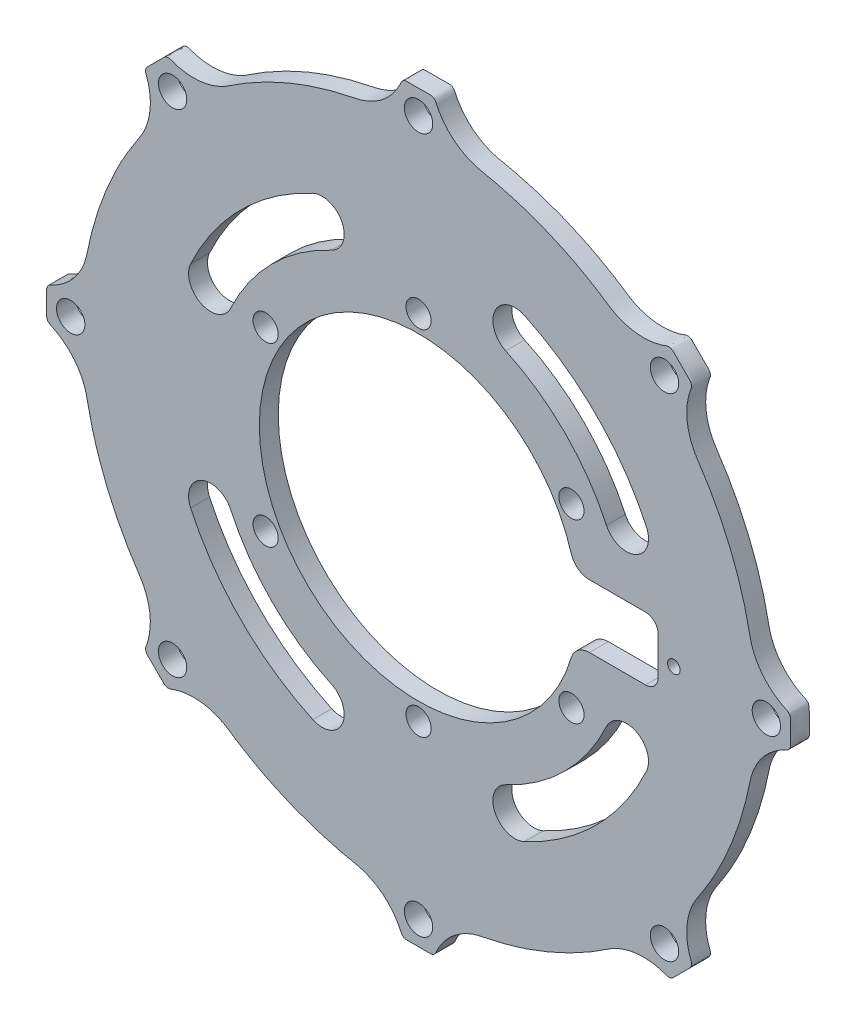
SolidWorks part; units mm, degrees
material "6061-T6 (SS)"
ref_plane "Front Plane" through (0, 0, 0) normal (0, 0, 1) x (1, 0, 0)
ref_plane "Top Plane" through (0, 0, 0) normal (0, 1, 0) x (1, 0, 0)
ref_plane "Right Plane" through (0, 0, 0) normal (1, 0, 0) x (0, 0, -1)
sketch "Sketch1" plane through (0, 0, 0) normal (0, 0, 1) x (1, 0, 0)
  line L0 (0, 0) -> (15.2936, 32.9713) construction
  line L1 (-3.9972, 40.3023) -> (0, 28) construction
  line L3 (38, -3) -> (38, 3) construction
  line L4 (38, -3) -> (38, 3)
  line L5 (36, 5) -> (27.0936, 5)
  line L6 (36, -5) -> (27.0936, -5)
  line L7 (0, 0) -> (0, 48) construction
  line L8 (-2.8886, 58.0903) -> (-2.7624, 58.3675)
  line L9 (-1.8466, 58.9658) -> (1.8466, 58.9658) construction
  line L10 (2.7624, 58.3675) -> (2.7687, 58.3533)
  line L11 (-5, 53.2658) -> (5, 53.2658) construction
  line L12 (40.3894, 43.0009) -> (43.0009, 40.3894) construction
  line L13 (39.3043, 43.2198) -> (39.3187, 43.2254) construction
  line L14 (43.2254, 39.3187) -> (43.2198, 39.3043) construction
  line L15 (58.9658, 1.8466) -> (58.9658, -1.8466) construction
  line L16 (58.3533, 2.7687) -> (58.3675, 2.7624) construction
  line L17 (58.3675, -2.7624) -> (58.3533, -2.7687) construction
  line L18 (43.0009, -40.3894) -> (40.3894, -43.0009) construction
  line L19 (43.2198, -39.3043) -> (43.2254, -39.3187) construction
  line L20 (39.3187, -43.2254) -> (39.3043, -43.2198) construction
  line L21 (1.8466, -58.9658) -> (-1.8466, -58.9658) construction
  line L22 (2.7687, -58.3533) -> (2.7624, -58.3675) construction
  line L23 (-2.7624, -58.3675) -> (-2.7687, -58.3533) construction
  line L24 (-40.3894, -43.0009) -> (-43.0009, -40.3894) construction
  line L25 (-39.3043, -43.2198) -> (-39.3187, -43.2254) construction
  line L26 (-43.2254, -39.3187) -> (-43.2198, -39.3043) construction
  line L27 (-58.9658, -1.8466) -> (-58.9658, 1.8466) construction
  line L28 (-58.3533, -2.7687) -> (-58.3675, -2.7624) construction
  line L29 (-58.3675, 2.7624) -> (-58.3533, 2.7687) construction
  line L30 (-43.0009, 40.3894) -> (-40.3894, 43.0009) construction
  line L31 (-43.2198, 39.3043) -> (-43.2254, 39.3187) construction
  line L32 (-39.3187, 43.2254) -> (-39.3043, 43.2198) construction
  line L33 (0, 0) -> (25.7002, 25.7002) construction
  arc A0 (-10.0483, 52.5479) -> (-30.0517, 44.2622) centre (0, 0) ccw construction
  circle A1 centre (0, 0) radius 28 construction
  arc A3 (24.2164, 7.1504) -> (24.2164, -7.1504) centre (0, 0) ccw
  arc A4 (38, 3) -> (34, 3) centre (36, 3) ccw construction
  arc A5 (34, -3) -> (38, -3) centre (36, -3) ccw construction
  arc A6 (36, -5) -> (38, -3) centre (36, -3) ccw
  arc A7 (38, 3) -> (36, 5) centre (36, 3) ccw
  arc A8 (27.0936, -5) -> (24.2164, -7.1504) centre (27.0936, -8) ccw
  arc A9 (27.0936, 5) -> (24.2164, 7.1504) centre (27.0936, 8) cw
  circle A10 centre (0, 0) radius 36.3456 construction
  arc A13 (15.2936, 32.9713) -> (32.9713, 15.2936) centre (0, 0) cw construction
  circle A72 centre (0, 0) radius 40.5 construction
  circle A81 centre (40.4993, -0.2374) radius 1
  arc A104 (-2.8886, 58.0903) -> (-10.0483, 52.5479) centre (-11.9265, 62.3699) cw construction
  arc A105 (2.7687, 58.3533) -> (10.0483, 52.5479) centre (11.9265, 62.3699) ccw construction
  arc A106 (39.3043, 43.2198) -> (30.0517, 44.2622) centre (35.6689, 52.5355) cw construction
  arc A107 (43.2198, 39.3043) -> (44.2622, 30.0517) centre (52.5355, 35.6689) ccw construction
  arc A108 (58.3533, 2.7687) -> (52.5479, 10.0483) centre (62.3699, 11.9265) cw construction
  arc A109 (58.3533, -2.7687) -> (52.5479, -10.0483) centre (62.3699, -11.9265) ccw construction
  arc A110 (43.2198, -39.3043) -> (44.2622, -30.0517) centre (52.5355, -35.6689) cw construction
  arc A111 (39.3043, -43.2198) -> (30.0517, -44.2622) centre (35.6689, -52.5355) ccw construction
  arc A112 (2.7687, -58.3533) -> (10.0483, -52.5479) centre (11.9265, -62.3699) cw construction
  arc A113 (-2.7687, -58.3533) -> (-10.0483, -52.5479) centre (-11.9265, -62.3699) ccw construction
  arc A114 (-39.3043, -43.2198) -> (-30.0517, -44.2622) centre (-35.6689, -52.5355) cw construction
  arc A115 (-43.2198, -39.3043) -> (-44.2622, -30.0517) centre (-52.5355, -35.6689) ccw construction
  arc A116 (-58.3533, -2.7687) -> (-52.5479, -10.0483) centre (-62.3699, -11.9265) cw construction
  arc A117 (-58.3533, 2.7687) -> (-52.5479, 10.0483) centre (-62.3699, 11.9265) ccw construction
  arc A118 (-43.2198, 39.3043) -> (-44.2622, 30.0517) centre (-52.5355, 35.6689) cw construction
  arc A119 (-39.3043, 43.2198) -> (-30.0517, 44.2622) centre (-35.6689, 52.5355) ccw construction
  arc A120 (30.0517, 44.2622) -> (10.0483, 52.5479) centre (0, 0) ccw construction
  arc A121 (52.5479, 10.0483) -> (44.2622, 30.0517) centre (0, 0) ccw construction
  arc A122 (10.0483, -52.5479) -> (30.0517, -44.2622) centre (0, 0) ccw construction
  arc A123 (44.2622, -30.0517) -> (52.5479, -10.0483) centre (0, 0) ccw construction
  arc A124 (-30.0517, -44.2622) -> (-10.0483, -52.5479) centre (0, 0) ccw construction
  arc A125 (-52.5479, -10.0483) -> (-44.2622, -30.0517) centre (0, 0) ccw construction
  arc A126 (-44.2622, 30.0517) -> (-52.5479, 10.0483) centre (0, 0) ccw construction
  arc A127 (1.8466, 58.9658) -> (2.7624, 58.3675) centre (1.8466, 57.9658) cw construction
  arc A128 (-2.7624, 58.3675) -> (-1.8466, 58.9658) centre (-1.8466, 57.9658) cw construction
  arc A129 (-43.0009, 40.3894) -> (-43.2254, 39.3187) centre (-42.2938, 39.6823) ccw construction
  arc A130 (-40.3894, 43.0009) -> (-39.3187, 43.2254) centre (-39.6823, 42.2938) cw construction
  arc A131 (-58.9658, 1.8466) -> (-58.3675, 2.7624) centre (-57.9658, 1.8466) cw construction
  arc A132 (-58.9658, -1.8466) -> (-58.3675, -2.7624) centre (-57.9658, -1.8466) ccw construction
  arc A133 (-43.0009, -40.3894) -> (-43.2254, -39.3187) centre (-42.2938, -39.6823) cw construction
  arc A134 (-40.3894, -43.0009) -> (-39.3187, -43.2254) centre (-39.6823, -42.2938) ccw construction
  arc A135 (-1.8466, -58.9658) -> (-2.7624, -58.3675) centre (-1.8466, -57.9658) cw construction
  arc A136 (1.8466, -58.9658) -> (2.7624, -58.3675) centre (1.8466, -57.9658) ccw construction
  arc A137 (43.0009, -40.3894) -> (43.2254, -39.3187) centre (42.2938, -39.6823) ccw construction
  arc A138 (40.3894, -43.0009) -> (39.3187, -43.2254) centre (39.6823, -42.2938) cw construction
  arc A139 (58.9658, -1.8466) -> (58.3675, -2.7624) centre (57.9658, -1.8466) cw construction
  arc A140 (58.9658, 1.8466) -> (58.3675, 2.7624) centre (57.9658, 1.8466) ccw construction
  arc A141 (43.0009, 40.3894) -> (43.2254, 39.3187) centre (42.2938, 39.6823) cw construction
  arc A142 (40.3894, 43.0009) -> (39.3187, 43.2254) centre (39.6823, 42.2938) ccw construction
  arc A143 (36.1463, 16.7664) -> (16.7664, 36.1463) centre (0, 0) ccw
  arc A144 (29.7962, 13.8209) -> (13.8209, 29.7962) centre (0, 0) ccw
  arc A145 (29.7962, 13.8209) -> (36.1463, 16.7664) centre (32.9713, 15.2936) ccw
  arc A146 (16.7664, 36.1463) -> (13.8209, 29.7962) centre (15.2936, 32.9713) ccw
  arc A147 (32.9713, -15.2936) -> (15.2936, -32.9713) centre (0, 0) cw construction
  arc A148 (16.7664, -36.1463) -> (36.1463, -16.7664) centre (0, 0) ccw
  arc A149 (13.8209, -29.7962) -> (29.7962, -13.8209) centre (0, 0) ccw
  arc A150 (13.8209, -29.7962) -> (16.7664, -36.1463) centre (15.2936, -32.9713) ccw
  arc A151 (36.1463, -16.7664) -> (29.7962, -13.8209) centre (32.9713, -15.2936) ccw
  arc A152 (-15.2936, -32.9713) -> (-32.9713, -15.2936) centre (0, 0) cw construction
  arc A153 (-36.1463, -16.7664) -> (-16.7664, -36.1463) centre (0, 0) ccw
  arc A154 (-29.7962, -13.8209) -> (-13.8209, -29.7962) centre (0, 0) ccw
  arc A155 (-29.7962, -13.8209) -> (-36.1463, -16.7664) centre (-32.9713, -15.2936) ccw
  arc A156 (-16.7664, -36.1463) -> (-13.8209, -29.7962) centre (-15.2936, -32.9713) ccw
  arc A157 (-32.9713, 15.2936) -> (-15.2936, 32.9713) centre (0, 0) cw construction
  arc A158 (-16.7664, 36.1463) -> (-36.1463, 16.7664) centre (0, 0) ccw
  arc A159 (-13.8209, 29.7962) -> (-29.7962, 13.8209) centre (0, 0) ccw
  arc A160 (-13.8209, 29.7962) -> (-16.7664, 36.1463) centre (-15.2936, 32.9713) ccw
  arc A161 (-36.1463, 16.7664) -> (-29.7962, 13.8209) centre (-32.9713, 15.2936) ccw
  spline S0 degree 3 poles (-2.8886, 58.0903) (-3.9043, 55.9453) (-5.5918, 54.2764) (-7.7481, 53.2847) (-8.2352, 53.0607) (-9.2456, 52.691) (-10.8423, 52.3981) (-11.8892, 52.165) (-12.4107, 52.0406) (-17.936, 50.7229) (-23.1839, 48.5492) (-28.0226, 45.574) (-28.4793, 45.2931) (-29.3844, 44.7177) (-30.7205, 43.7957) (-31.6964, 43.3428) (-32.1993, 43.1567) (-34.5203, 42.2981) (-36.9949, 42.3196) (-39.3007, 43.2183) (-39.3011, 43.2185) (-39.3019, 43.2188) (-39.3031, 43.2193) (-39.3039, 43.2196) (-39.3043, 43.2198) (-39.3047, 43.2199) (-39.3055, 43.2202) (-39.3067, 43.2207) (-39.3075, 43.221) (-39.3079, 43.2212) (-39.3103, 43.2221) (-39.3127, 43.223) (-39.3151, 43.224) (-39.3155, 43.2241) (-39.3163, 43.2245) (-39.3175, 43.2249) (-39.3183, 43.2252) (-39.3187, 43.2254) (-39.3191, 43.2255) (-39.3199, 43.2259) (-39.3211, 43.2263) (-39.3219, 43.2266) (-39.3224, 43.2268) (-39.5998, 43.3338) (-39.8966, 43.3148) (-40.1582, 43.1733) (-40.1864, 43.158) (-40.2413, 43.1248) (-40.3214, 43.0689) (-40.3667, 43.0236) (-40.3894, 43.0009) (-40.412, 42.9783) (-40.4573, 42.933) (-40.5253, 42.865) (-40.5706, 42.8197) (-40.5933, 42.797) (-41.3279, 42.0624) (-42.0624, 41.3279) (-42.797, 40.5933) (-42.8197, 40.5706) (-42.865, 40.5253) (-42.933, 40.4573) (-42.9783, 40.412) (-43.0009, 40.3894) (-43.0236, 40.3667) (-43.0689, 40.3214) (-43.1248, 40.2413) (-43.158, 40.1864) (-43.1733, 40.1582) (-43.3148, 39.8966) (-43.3338, 39.5998) (-43.2268, 39.3224) (-43.2266, 39.3219) (-43.2263, 39.3211) (-43.2259, 39.3199) (-43.2255, 39.3191) (-43.2254, 39.3187) (-43.2252, 39.3183) (-43.2249, 39.3175) (-43.2245, 39.3163) (-43.2241, 39.3155) (-43.224, 39.3151) (-43.223, 39.3127) (-43.2221, 39.3103) (-43.2212, 39.3079) (-43.221, 39.3075) (-43.2207, 39.3067) (-43.2202, 39.3055) (-43.2199, 39.3047) (-43.2198, 39.3043) (-43.2196, 39.3039) (-43.2193, 39.3031) (-43.2188, 39.3019) (-43.2185, 39.3011) (-43.2183, 39.3007) (-42.3196, 36.9949) (-42.2981, 34.5203) (-43.1567, 32.1993) (-43.3428, 31.6964) (-43.7957, 30.7205) (-44.7177, 29.3844) (-45.2931, 28.4793) (-45.574, 28.0226) (-48.5492, 23.1839) (-50.7229, 17.936) (-52.0406, 12.4107) (-52.165, 11.8892) (-52.3981, 10.8423) (-52.691, 9.2456) (-53.0607, 8.2352) (-53.2847, 7.7481) (-54.3188, 5.4997) (-56.0838, 3.7651) (-58.3498, 2.7702) (-58.3502, 2.77) (-58.3509, 2.7697) (-58.3521, 2.7692) (-58.3529, 2.7688) (-58.3533, 2.7687) (-58.3537, 2.7685) (-58.3545, 2.7681) (-58.3557, 2.7676) (-58.3565, 2.7673) (-58.3569, 2.7671) (-58.3592, 2.7661) (-58.3616, 2.765) (-58.364, 2.764) (-58.3644, 2.7638) (-58.3651, 2.7635) (-58.3663, 2.7629) (-58.3671, 2.7626) (-58.3675, 2.7624) (-58.3679, 2.7623) (-58.3687, 2.7619) (-58.3699, 2.7614) (-58.3707, 2.761) (-58.3711, 2.7609) (-58.643, 2.6403) (-58.8394, 2.417) (-58.9243, 2.132) (-58.9334, 2.1013) (-58.9487, 2.039) (-58.9658, 1.9428) (-58.9658, 1.8787) (-58.9658, 1.8466) (-58.9658, 1.8146) (-58.9658, 1.7505) (-58.9658, 1.6544) (-58.9658, 1.5903) (-58.9658, 1.5583) (-58.9658, 0.5194) (-58.9658, -0.5194) (-58.9658, -1.5583) (-58.9658, -1.5903) (-58.9658, -1.6544) (-58.9658, -1.7505) (-58.9658, -1.8146) (-58.9658, -1.8466) (-58.9658, -1.8787) (-58.9658, -1.9428) (-58.9487, -2.039) (-58.9334, -2.1013) (-58.9243, -2.132) (-58.8394, -2.417) (-58.643, -2.6403) (-58.3711, -2.7609) (-58.3707, -2.761) (-58.3699, -2.7614) (-58.3687, -2.7619) (-58.3679, -2.7623) (-58.3675, -2.7624) (-58.3671, -2.7626) (-58.3663, -2.7629) (-58.3651, -2.7635) (-58.3644, -2.7638) (-58.364, -2.764) (-58.3616, -2.765) (-58.3592, -2.7661) (-58.3569, -2.7671) (-58.3565, -2.7673) (-58.3557, -2.7676) (-58.3545, -2.7681) (-58.3537, -2.7685) (-58.3533, -2.7687) (-58.3529, -2.7688) (-58.3521, -2.7692) (-58.3509, -2.7697) (-58.3502, -2.77) (-58.3498, -2.7702) (-56.0838, -3.7651) (-54.3188, -5.4997) (-53.2847, -7.7481) (-53.0607, -8.2352) (-52.691, -9.2456) (-52.3981, -10.8423) (-52.165, -11.8892) (-52.0406, -12.4107) (-50.7229, -17.936) (-48.5492, -23.1839) (-45.574, -28.0226) (-45.2931, -28.4793) (-44.7177, -29.3844) (-43.7957, -30.7205) (-43.3428, -31.6964) (-43.1567, -32.1993) (-42.2981, -34.5203) (-42.3196, -36.9949) (-43.2183, -39.3007) (-43.2185, -39.3011) (-43.2188, -39.3019) (-43.2193, -39.3031) (-43.2196, -39.3039) (-43.2198, -39.3043) (-43.2199, -39.3047) (-43.2202, -39.3055) (-43.2207, -39.3067) (-43.221, -39.3075) (-43.2212, -39.3079) (-43.2221, -39.3103) (-43.223, -39.3127) (-43.224, -39.3151) (-43.2241, -39.3155) (-43.2245, -39.3163) (-43.2249, -39.3175) (-43.2252, -39.3183) (-43.2254, -39.3187) (-43.2255, -39.3191) (-43.2259, -39.3199) (-43.2263, -39.3211) (-43.2266, -39.3219) (-43.2268, -39.3224) (-43.3338, -39.5998) (-43.3148, -39.8966) (-43.1733, -40.1582) (-43.158, -40.1864) (-43.1248, -40.2413) (-43.0689, -40.3214) (-43.0236, -40.3667) (-43.0009, -40.3894) (-42.9783, -40.412) (-42.933, -40.4573) (-42.865, -40.5253) (-42.8197, -40.5706) (-42.797, -40.5933) (-42.0624, -41.3279) (-41.3279, -42.0624) (-40.5933, -42.797) (-40.5706, -42.8197) (-40.5253, -42.865) (-40.4573, -42.933) (-40.412, -42.9783) (-40.3894, -43.0009) (-40.3667, -43.0236) (-40.3214, -43.0689) (-40.2413, -43.1248) (-40.1864, -43.158) (-40.1582, -43.1733) (-39.8966, -43.3148) (-39.5998, -43.3338) (-39.3224, -43.2268) (-39.3219, -43.2266) (-39.3211, -43.2263) (-39.3199, -43.2259) (-39.3191, -43.2255) (-39.3187, -43.2254) (-39.3183, -43.2252) (-39.3175, -43.2249) (-39.3163, -43.2245) (-39.3155, -43.2241) (-39.3151, -43.224) (-39.3127, -43.223) (-39.3103, -43.2221) (-39.3079, -43.2212) (-39.3075, -43.221) (-39.3067, -43.2207) (-39.3055, -43.2202) (-39.3047, -43.2199) (-39.3043, -43.2198) (-39.3039, -43.2196) (-39.3031, -43.2193) (-39.3019, -43.2188) (-39.3011, -43.2185) (-39.3007, -43.2183) (-36.9949, -42.3196) (-34.5203, -42.2981) (-32.1993, -43.1567) (-31.6964, -43.3428) (-30.7205, -43.7957) (-29.3844, -44.7177) (-28.4793, -45.2931) (-28.0226, -45.574) (-23.1839, -48.5492) (-17.936, -50.7229) (-12.4107, -52.0406) (-11.8892, -52.165) (-10.8423, -52.3981) (-9.2456, -52.691) (-8.2352, -53.0607) (-7.7481, -53.2847) (-5.4997, -54.3188) (-3.7651, -56.0838) (-2.7702, -58.3498) (-2.77, -58.3502) (-2.7697, -58.3509) (-2.7692, -58.3521) (-2.7688, -58.3529) (-2.7687, -58.3533) (-2.7685, -58.3537) (-2.7681, -58.3545) (-2.7676, -58.3557) (-2.7673, -58.3565) (-2.7671, -58.3569) (-2.7661, -58.3592) (-2.765, -58.3616) (-2.764, -58.364) (-2.7638, -58.3644) (-2.7635, -58.3651) (-2.7629, -58.3663) (-2.7626, -58.3671) (-2.7624, -58.3675) (-2.7623, -58.3679) (-2.7619, -58.3687) (-2.7614, -58.3699) (-2.761, -58.3707) (-2.7609, -58.3711) (-2.6403, -58.643) (-2.417, -58.8394) (-2.132, -58.9243) (-2.1013, -58.9334) (-2.039, -58.9487) (-1.9428, -58.9658) (-1.8787, -58.9658) (-1.8466, -58.9658) (-1.8146, -58.9658) (-1.7505, -58.9658) (-1.6544, -58.9658) (-1.5903, -58.9658) (-1.5583, -58.9658) (-0.5194, -58.9658) (0.5194, -58.9658) (1.5583, -58.9658) (1.5903, -58.9658) (1.6544, -58.9658) (1.7505, -58.9658) (1.8146, -58.9658) (1.8466, -58.9658) (1.8787, -58.9658) (1.9428, -58.9658) (2.039, -58.9487) (2.1013, -58.9334) (2.132, -58.9243) (2.417, -58.8394) (2.6403, -58.643) (2.7609, -58.3711) (2.761, -58.3707) (2.7614, -58.3699) (2.7619, -58.3687) (2.7623, -58.3679) (2.7624, -58.3675) (2.7626, -58.3671) (2.7629, -58.3663) (2.7635, -58.3651) (2.7638, -58.3644) (2.764, -58.364) (2.765, -58.3616) (2.7661, -58.3592) (2.7671, -58.3569) (2.7673, -58.3565) (2.7676, -58.3557) (2.7681, -58.3545) (2.7685, -58.3537) (2.7687, -58.3533) (2.7688, -58.3529) (2.7692, -58.3521) (2.7697, -58.3509) (2.77, -58.3502) (2.7702, -58.3498) (3.7651, -56.0838) (5.4997, -54.3188) (7.7481, -53.2847) (8.2352, -53.0607) (9.2456, -52.691) (10.8423, -52.3981) (11.8892, -52.165) (12.4107, -52.0406) (17.936, -50.7229) (23.1839, -48.5492) (28.0226, -45.574) (28.4793, -45.2931) (29.3844, -44.7177) (30.7205, -43.7957) (31.6964, -43.3428) (32.1993, -43.1567) (34.5203, -42.2981) (36.9949, -42.3196) (39.3007, -43.2183) (39.3011, -43.2185) (39.3019, -43.2188) (39.3031, -43.2193) (39.3039, -43.2196) (39.3043, -43.2198) (39.3047, -43.2199) (39.3055, -43.2202) (39.3067, -43.2207) (39.3075, -43.221) (39.3079, -43.2212) (39.3103, -43.2221) (39.3127, -43.223) (39.3151, -43.224) (39.3155, -43.2241) (39.3163, -43.2245) (39.3175, -43.2249) (39.3183, -43.2252) (39.3187, -43.2254) (39.3191, -43.2255) (39.3199, -43.2259) (39.3211, -43.2263) (39.3219, -43.2266) (39.3224, -43.2268) (39.5998, -43.3338) (39.8966, -43.3148) (40.1582, -43.1733) (40.1864, -43.158) (40.2413, -43.1248) (40.3214, -43.0689) (40.3667, -43.0236) (40.3894, -43.0009) (40.412, -42.9783) (40.4573, -42.933) (40.5253, -42.865) (40.5706, -42.8197) (40.5933, -42.797) (41.3279, -42.0624) (42.0624, -41.3279) (42.797, -40.5933) (42.8197, -40.5706) (42.865, -40.5253) (42.933, -40.4573) (42.9783, -40.412) (43.0009, -40.3894) (43.0236, -40.3667) (43.0689, -40.3214) (43.1248, -40.2413) (43.158, -40.1864) (43.1733, -40.1582) (43.3148, -39.8966) (43.3338, -39.5998) (43.2268, -39.3224) (43.2266, -39.3219) (43.2263, -39.3211) (43.2259, -39.3199) (43.2255, -39.3191) (43.2254, -39.3187) (43.2252, -39.3183) (43.2249, -39.3175) (43.2245, -39.3163) (43.2241, -39.3155) (43.224, -39.3151) (43.223, -39.3127) (43.2221, -39.3103) (43.2212, -39.3079) (43.221, -39.3075) (43.2207, -39.3067) (43.2202, -39.3055) (43.2199, -39.3047) (43.2198, -39.3043) (43.2196, -39.3039) (43.2193, -39.3031) (43.2188, -39.3019) (43.2185, -39.3011) (43.2183, -39.3007) (42.3196, -36.9949) (42.2981, -34.5203) (43.1567, -32.1993) (43.3428, -31.6964) (43.7957, -30.7205) (44.7177, -29.3844) (45.2931, -28.4793) (45.574, -28.0226) (48.5492, -23.1839) (50.7229, -17.936) (52.0406, -12.4107) (52.165, -11.8892) (52.3981, -10.8423) (52.691, -9.2456) (53.0607, -8.2352) (53.2847, -7.7481) (54.3188, -5.4997) (56.0838, -3.7651) (58.3498, -2.7702) (58.3502, -2.77) (58.3509, -2.7697) (58.3521, -2.7692) (58.3529, -2.7688) (58.3533, -2.7687) (58.3537, -2.7685) (58.3545, -2.7681) (58.3557, -2.7676) (58.3565, -2.7673) (58.3569, -2.7671) (58.3592, -2.7661) (58.3616, -2.765) (58.364, -2.764) (58.3644, -2.7638) (58.3651, -2.7635) (58.3663, -2.7629) (58.3671, -2.7626) (58.3675, -2.7624) (58.3679, -2.7623) (58.3687, -2.7619) (58.3699, -2.7614) (58.3707, -2.761) (58.3711, -2.7609) (58.643, -2.6403) (58.8394, -2.417) (58.9243, -2.132) (58.9334, -2.1013) (58.9487, -2.039) (58.9658, -1.9428) (58.9658, -1.8787) (58.9658, -1.8466) (58.9658, -1.8146) (58.9658, -1.7505) (58.9658, -1.6544) (58.9658, -1.5903) (58.9658, -1.5583) (58.9658, -0.5194) (58.9658, 0.5194) (58.9658, 1.5583) (58.9658, 1.5903) (58.9658, 1.6544) (58.9658, 1.7505) (58.9658, 1.8146) (58.9658, 1.8466) (58.9658, 1.8787) (58.9658, 1.9428) (58.9487, 2.039) (58.9334, 2.1013) (58.9243, 2.132) (58.8394, 2.417) (58.643, 2.6403) (58.3711, 2.7609) (58.3707, 2.761) (58.3699, 2.7614) (58.3687, 2.7619) (58.3679, 2.7623) (58.3675, 2.7624) (58.3671, 2.7626) (58.3663, 2.7629) (58.3651, 2.7635) (58.3644, 2.7638) (58.364, 2.764) (58.3616, 2.765) (58.3592, 2.7661) (58.3569, 2.7671) (58.3565, 2.7673) (58.3557, 2.7676) (58.3545, 2.7681) (58.3537, 2.7685) (58.3533, 2.7687) (58.3529, 2.7688) (58.3521, 2.7692) (58.3509, 2.7697) (58.3502, 2.77) (58.3498, 2.7702) (56.0838, 3.7651) (54.3188, 5.4997) (53.2847, 7.7481) (53.0607, 8.2352) (52.691, 9.2456) (52.3981, 10.8423) (52.165, 11.8892) (52.0406, 12.4107) (50.7229, 17.936) (48.5492, 23.1839) (45.574, 28.0226) (45.2931, 28.4793) (44.7177, 29.3844) (43.7957, 30.7205) (43.3428, 31.6964) (43.1567, 32.1993) (42.2981, 34.5203) (42.3196, 36.9949) (43.2183, 39.3007) (43.2185, 39.3011) (43.2188, 39.3019) (43.2193, 39.3031) (43.2196, 39.3039) (43.2198, 39.3043) (43.2199, 39.3047) (43.2202, 39.3055) (43.2207, 39.3067) (43.221, 39.3075) (43.2212, 39.3079) (43.2221, 39.3103) (43.223, 39.3127) (43.224, 39.3151) (43.2241, 39.3155) (43.2245, 39.3163) (43.2249, 39.3175) (43.2252, 39.3183) (43.2254, 39.3187) (43.2255, 39.3191) (43.2259, 39.3199) (43.2263, 39.3211) (43.2266, 39.3219) (43.2268, 39.3224) (43.3338, 39.5998) (43.3148, 39.8966) (43.1733, 40.1582) (43.158, 40.1864) (43.1248, 40.2413) (43.0689, 40.3214) (43.0236, 40.3667) (43.0009, 40.3894) (42.9783, 40.412) (42.933, 40.4573) (42.865, 40.5253) (42.8197, 40.5706) (42.797, 40.5933) (42.0624, 41.3279) (41.3279, 42.0624) (40.5933, 42.797) (40.5706, 42.8197) (40.5253, 42.865) (40.4573, 42.933) (40.412, 42.9783) (40.3894, 43.0009) (40.3667, 43.0236) (40.3214, 43.0689) (40.2413, 43.1248) (40.1864, 43.158) (40.1582, 43.1733) (39.8966, 43.3148) (39.5998, 43.3338) (39.3224, 43.2268) (39.3219, 43.2266) (39.3211, 43.2263) (39.3199, 43.2259) (39.3191, 43.2255) (39.3187, 43.2254) (39.3183, 43.2252) (39.3175, 43.2249) (39.3163, 43.2245) (39.3155, 43.2241) (39.3151, 43.224) (39.3127, 43.223) (39.3103, 43.2221) (39.3079, 43.2212) (39.3075, 43.221) (39.3067, 43.2207) (39.3055, 43.2202) (39.3047, 43.2199) (39.3043, 43.2198) (39.3039, 43.2196) (39.3031, 43.2193) (39.3019, 43.2188) (39.3011, 43.2185) (39.3007, 43.2183) (36.9949, 42.3196) (34.5203, 42.2981) (32.1993, 43.1567) (31.6964, 43.3428) (30.7205, 43.7957) (29.3844, 44.7177) (28.4793, 45.2931) (28.0226, 45.574) (23.1839, 48.5492) (17.936, 50.7229) (12.4107, 52.0406) (11.8892, 52.165) (10.8423, 52.3981) (9.2456, 52.691) (8.2352, 53.0607) (7.7481, 53.2847) (5.5918, 54.2764) (3.9043, 55.9453) (2.8886, 58.0903) (2.8604, 58.1497) (2.8053, 58.2691) (2.7273, 58.4532) (2.6522, 58.562) (2.6097, 58.6121) (2.4833, 58.7614) (2.3195, 58.8684) (2.132, 58.9243) (2.1013, 58.9334) (2.039, 58.9487) (1.9428, 58.9658) (1.8787, 58.9658) (1.8466, 58.9658) (1.8146, 58.9658) (1.7505, 58.9658) (1.6544, 58.9658) (1.5903, 58.9658) (1.5583, 58.9658) (0.5194, 58.9658) (-0.5194, 58.9658) (-1.5583, 58.9658) (-1.5903, 58.9658) (-1.6544, 58.9658) (-1.7505, 58.9658) (-1.8146, 58.9658) (-1.8466, 58.9658) (-1.8787, 58.9658) (-1.9428, 58.9658) (-2.039, 58.9487) (-2.1013, 58.9334) (-2.132, 58.9243) (-2.3195, 58.8684) (-2.4833, 58.7614) (-2.6097, 58.6121) (-2.6522, 58.562) (-2.7273, 58.4532) (-2.8053, 58.2691) (-2.8604, 58.1497) (-2.8886, 58.0903) (-3.9043, 55.9453) (-5.5918, 54.2764) knots -0.000527 0 0 0 0.018272 0.018272 0.018272 0.022573 0.026874 0.031175 0.031175 0.031175 0.076354 0.076354 0.076354 0.080654 0.084955 0.089256 0.089256 0.089256 0.108243 0.108243 0.108243 0.108247 0.10825 0.108253 0.108253 0.108253 0.108257 0.10826 0.108264 0.108264 0.108264 0.108285 0.108285 0.108285 0.108288 0.108291 0.108295 0.108295 0.108295 0.108298 0.108302 0.108305 0.108305 0.108305 0.110545 0.110545 0.110545 0.110802 0.111059 0.111316 0.111316 0.111316 0.111573 0.11183 0.112087 0.112087 0.112087 0.120419 0.120419 0.120419 0.120676 0.120933 0.12119 0.12119 0.12119 0.121447 0.121704 0.121961 0.121961 0.121961 0.1242 0.1242 0.1242 0.124204 0.124207 0.124211 0.124211 0.124211 0.124214 0.124218 0.124221 0.124221 0.124221 0.124242 0.124242 0.124242 0.124245 0.124249 0.124252 0.124252 0.124252 0.124256 0.124259 0.124262 0.124262 0.124262 0.14325 0.14325 0.14325 0.14755 0.151851 0.156152 0.156152 0.156152 0.201331 0.201331 0.201331 0.205632 0.209932 0.214233 0.214233 0.214233 0.23322 0.23322 0.23322 0.233224 0.233227 0.233231 0.233231 0.233231 0.233234 0.233237 0.233241 0.233241 0.233241 0.233262 0.233262 0.233262 0.233265 0.233269 0.233272 0.233272 0.233272 0.233275 0.233279 0.233282 0.233282 0.233282 0.235522 0.235522 0.235522 0.235779 0.236036 0.236293 0.236293 0.236293 0.23655 0.236807 0.237064 0.237064 0.237064 0.245396 0.245396 0.245396 0.245653 0.24591 0.246167 0.246167 0.246167 0.246424 0.246681 0.246938 0.246938 0.246938 0.249177 0.249177 0.249177 0.249181 0.249184 0.249188 0.249188 0.249188 0.249191 0.249195 0.249198 0.249198 0.249198 0.249219 0.249219 0.249219 0.249222 0.249226 0.249229 0.249229 0.249229 0.249233 0.249236 0.24924 0.24924 0.24924 0.268227 0.268227 0.268227 0.272527 0.276828 0.281129 0.281129 0.281129 0.326308 0.326308 0.326308 0.330609 0.33491 0.33921 0.33921 0.33921 0.358197 0.358197 0.358197 0.358201 0.358204 0.358208 0.358208 0.358208 0.358211 0.358215 0.358218 0.358218 0.358218 0.358239 0.358239 0.358239 0.358242 0.358246 0.358249 0.358249 0.358249 0.358253 0.358256 0.35826 0.35826 0.35826 0.360499 0.360499 0.360499 0.360756 0.361013 0.36127 0.36127 0.36127 0.361527 0.361784 0.362041 0.362041 0.362041 0.370373 0.370373 0.370373 0.37063 0.370887 0.371144 0.371144 0.371144 0.371401 0.371658 0.371915 0.371915 0.371915 0.374155 0.374155 0.374155 0.374158 0.374161 0.374165 0.374165 0.374165 0.374168 0.374172 0.374175 0.374175 0.374175 0.374196 0.374196 0.374196 0.374199 0.374203 0.374206 0.374206 0.374206 0.37421 0.374213 0.374217 0.374217 0.374217 0.393204 0.393204 0.393204 0.397505 0.401805 0.406106 0.406106 0.406106 0.451285 0.451285 0.451285 0.455586 0.459887 0.464187 0.464187 0.464187 0.483175 0.483175 0.483175 0.483178 0.483181 0.483185 0.483185 0.483185 0.483188 0.483192 0.483195 0.483195 0.483195 0.483216 0.483216 0.483216 0.483219 0.483223 0.483226 0.483226 0.483226 0.48323 0.483233 0.483237 0.483237 0.483237 0.485476 0.485476 0.485476 0.485733 0.48599 0.486247 0.486247 0.486247 0.486504 0.486761 0.487018 0.487018 0.487018 0.49535 0.49535 0.49535 0.495607 0.495864 0.496121 0.496121 0.496121 0.496378 0.496635 0.496892 0.496892 0.496892 0.499132 0.499132 0.499132 0.499135 0.499139 0.499142 0.499142 0.499142 0.499146 0.499149 0.499152 0.499152 0.499152 0.499173 0.499173 0.499173 0.499177 0.49918 0.499184 0.499184 0.499184 0.499187 0.49919 0.499194 0.499194 0.499194 0.518181 0.518181 0.518181 0.522482 0.526783 0.531083 0.531083 0.531083 0.576262 0.576262 0.576262 0.580563 0.584864 0.589165 0.589165 0.589165 0.608152 0.608152 0.608152 0.608155 0.608159 0.608162 0.608162 0.608162 0.608166 0.608169 0.608172 0.608172 0.608172 0.608193 0.608193 0.608193 0.608197 0.6082 0.608203 0.608203 0.608203 0.608207 0.60821 0.608214 0.608214 0.608214 0.610453 0.610453 0.610453 0.61071 0.610967 0.611224 0.611224 0.611224 0.611481 0.611738 0.611995 0.611995 0.611995 0.620328 0.620328 0.620328 0.620585 0.620842 0.621099 0.621099 0.621099 0.621356 0.621613 0.62187 0.62187 0.62187 0.624109 0.624109 0.624109 0.624112 0.624116 0.624119 0.624119 0.624119 0.624123 0.624126 0.62413 0.62413 0.62413 0.62415 0.62415 0.62415 0.624154 0.624157 0.624161 0.624161 0.624161 0.624164 0.624168 0.624171 0.624171 0.624171 0.643158 0.643158 0.643158 0.647459 0.65176 0.65606 0.65606 0.65606 0.701239 0.701239 0.701239 0.70554 0.709841 0.714142 0.714142 0.714142 0.733129 0.733129 0.733129 0.733132 0.733136 0.733139 0.733139 0.733139 0.733143 0.733146 0.73315 0.73315 0.73315 0.73317 0.73317 0.73317 0.733174 0.733177 0.733181 0.733181 0.733181 0.733184 0.733188 0.733191 0.733191 0.733191 0.73543 0.73543 0.73543 0.735687 0.735944 0.736201 0.736201 0.736201 0.736458 0.736715 0.736972 0.736972 0.736972 0.745305 0.745305 0.745305 0.745562 0.745819 0.746076 0.746076 0.746076 0.746333 0.74659 0.746847 0.746847 0.746847 0.749086 0.749086 0.749086 0.749089 0.749093 0.749096 0.749096 0.749096 0.7491 0.749103 0.749107 0.749107 0.749107 0.749127 0.749127 0.749127 0.749131 0.749134 0.749138 0.749138 0.749138 0.749141 0.749145 0.749148 0.749148 0.749148 0.768135 0.768135 0.768135 0.772436 0.776737 0.781038 0.781038 0.781038 0.826217 0.826217 0.826217 0.830517 0.834818 0.839119 0.839119 0.839119 0.858106 0.858106 0.858106 0.858109 0.858113 0.858116 0.858116 0.858116 0.85812 0.858123 0.858127 0.858127 0.858127 0.858147 0.858147 0.858147 0.858151 0.858154 0.858158 0.858158 0.858158 0.858161 0.858165 0.858168 0.858168 0.858168 0.860408 0.860408 0.860408 0.860665 0.860921 0.861178 0.861178 0.861178 0.861435 0.861692 0.861949 0.861949 0.861949 0.870282 0.870282 0.870282 0.870539 0.870796 0.871053 0.871053 0.871053 0.87131 0.871567 0.871824 0.871824 0.871824 0.874063 0.874063 0.874063 0.874067 0.87407 0.874074 0.874074 0.874074 0.874077 0.87408 0.874084 0.874084 0.874084 0.874105 0.874105 0.874105 0.874108 0.874112 0.874115 0.874115 0.874115 0.874118 0.874122 0.874125 0.874125 0.874125 0.893112 0.893112 0.893112 0.897413 0.901714 0.906015 0.906015 0.906015 0.951194 0.951194 0.951194 0.955495 0.959795 0.964096 0.964096 0.964096 0.982368 0.982368 0.982368 0.982896 0.983423 0.98395 0.98395 0.98395 0.985476 0.985476 0.985476 0.985733 0.98599 0.986247 0.986247 0.986247 0.986504 0.986761 0.987018 0.987018 0.987018 0.99535 0.99535 0.99535 0.995607 0.995864 0.996121 0.996121 0.996121 0.996378 0.996635 0.996892 0.996892 0.996892 0.998418 0.998418 0.998418 0.998945 0.999473 1 1 1 1.018272 1.018272 1.018272 weights 1 0.959869 0.959869 1 1 1 1 1 1 0.991634 0.991634 1 1 1 1 1 1 0.956557 0.956557 1 1 1 1 1 1 1 1 1 1 1 1 1 1 1 1 1 1 1 1 1 1 1 1 0.938724 0.938724 1 1 1 1 1 1 1 1 1 1 1 1 1 1 1 1 1 1 1 1 1 1 1 1 0.938724 0.938724 1 1 1 1 1 1 1 1 1 1 1 1 1 1 1 1 1 1 1 1 1 1 1 1 0.956557 0.956557 1 1 1 1 1 1 0.991634 0.991634 1 1 1 1 1 1 0.956557 0.956557 1 1 1 1 1 1 1 1 1 1 1 1 1 1 1 1 1 1 1 1 1 1 1 1 0.938724 0.938724 1 1 1 1 1 1 1 1 1 1 1 1 1 1 1 1 1 1 1 1 1 1 1 1 0.938724 0.938724 1 1 1 1 1 1 1 1 1 1 1 1 1 1 1 1 1 1 1 1 1 1 1 1 0.956557 0.956557 1 1 1 1 1 1 0.991634 0.991634 1 1 1 1 1 1 0.956557 0.956557 1 1 1 1 1 1 1 1 1 1 1 1 1 1 1 1 1 1 1 1 1 1 1 1 0.938724 0.938724 1 1 1 1 1 1 1 1 1 1 1 1 1 1 1 1 1 1 1 1 1 1 1 1 0.938724 0.938724 1 1 1 1 1 1 1 1 1 1 1 1 1 1 1 1 1 1 1 1 1 1 1 1 0.956557 0.956557 1 1 1 1 1 1 0.991634 0.991634 1 1 1 1 1 1 0.956557 0.956557 1 1 1 1 1 1 1 1 1 1 1 1 1 1 1 1 1 1 1 1 1 1 1 1 0.938724 0.938724 1 1 1 1 1 1 1 1 1 1 1 1 1 1 1 1 1 1 1 1 1 1 1 1 0.938724 0.938724 1 1 1 1 1 1 1 1 1 1 1 1 1 1 1 1 1 1 1 1 1 1 1 1 0.956557 0.956557 1 1 1 1 1 1 0.991634 0.991634 1 1 1 1 1 1 0.956557 0.956557 1 1 1 1 1 1 1 1 1 1 1 1 1 1 1 1 1 1 1 1 1 1 1 1 0.938724 0.938724 1 1 1 1 1 1 1 1 1 1 1 1 1 1 1 1 1 1 1 1 1 1 1 1 0.938724 0.938724 1 1 1 1 1 1 1 1 1 1 1 1 1 1 1 1 1 1 1 1 1 1 1 1 0.956557 0.956557 1 1 1 1 1 1 0.991634 0.991634 1 1 1 1 1 1 0.956557 0.956557 1 1 1 1 1 1 1 1 1 1 1 1 1 1 1 1 1 1 1 1 1 1 1 1 0.938724 0.938724 1 1 1 1 1 1 1 1 1 1 1 1 1 1 1 1 1 1 1 1 1 1 1 1 0.938724 0.938724 1 1 1 1 1 1 1 1 1 1 1 1 1 1 1 1 1 1 1 1 1 1 1 1 0.956557 0.956557 1 1 1 1 1 1 0.991634 0.991634 1 1 1 1 1 1 0.956557 0.956557 1 1 1 1 1 1 1 1 1 1 1 1 1 1 1 1 1 1 1 1 1 1 1 1 0.938724 0.938724 1 1 1 1 1 1 1 1 1 1 1 1 1 1 1 1 1 1 1 1 1 1 1 1 0.938724 0.938724 1 1 1 1 1 1 1 1 1 1 1 1 1 1 1 1 1 1 1 1 1 1 1 1 0.956557 0.956557 1 1 1 1 1 1 0.991634 0.991634 1 1 1 1 1 1 0.959869 0.959869 1 1 1 1 1 1 0.972283 0.972283 1 1 1 1 1 1 1 1 1 1 1 1 1 1 1 1 1 1 1 1 1 1 1 1 0.972283 0.972283 1 1 1 1 1 1 0.959869 0.959869 only from (-2.8886, 58.0903) to (-2.8886, 58.0903)
  point P4 (0, 28)
  point P5 (24.2487, 14)
  point P9 (24.2487, -14)
  point P10 (0, -28)
  point P11 (-24.2487, -14)
  point P12 (-24.2487, 14)
  point P13 (0, 0)
  point P29 (25.7002, 25.7002)
  point P44 (25.7002, -25.7002)
  point P51 (-25.7002, -25.7002)
  point P58 (-25.7002, 25.7002)
  point P63 (0, 0)
  point P154 (0, 0)
  point P157 (0, 48)
  point P216 (0, 0)
  point P228 (2.5, 58.9658)
  point P285 (0, 0)
  point P288 (-2.5, 58.9658)
  point P317 (39.0081, 39.0081)
  point P318 (0, 55.1658)
  point P319 (0, 24)
  point P320 (55.1658, 0)
  point P323 (39.0081, -39.0081)
  point P324 (0, -55.1658)
  point P325 (-39.0081, -39.0081)
  point P326 (-55.1658, 0)
  point P327 (-39.0081, 39.0081)
  point P328 (0, 0)
  dimension "D1" = 56
  dimension "D2" = 107
  dimension "D3" = 6
  dimension "D4" = 50.5
  dimension "D5" = 3
  dimension "D6" = 2
  dimension "D7" = 40.4993
  dimension "D8" = 0.2374
  dimension "D9" = 18
  dimension "81" = 81
  dimension "D10" = 3.5
  dimension "D13" = 5.7
  dimension "D16" = 10
  dimension "D19" = 1
  dimension "D20" = 1
  dimension "D12" = 48
  dimension "D14" = 5
  dimension "D15" = 10
  dimension "D18" = 3.8
  dimension "D21" = 8
  dimension "D11" = 25
  dimension "D22" = 45
  dimension "D17" = 8
  dimension "D23" = 4
extrude "Boss-Extrude1" add sketch "Sketch1" along normal blind 3
hole_wizard "Ø4.0mm Dowel Hole1" positions "Sketch4" profile "Sketch5" hole size "Ø4.0" standard "ISO"
sketch "Sketch4" plane through (0, 0, 3) normal (0, 0, 1) x (1, 0, 0)
  point P0 (0, 28)
  point P3 (24.2487, 14)
  point P6 (24.2487, -14)
  point P9 (0, -28)
  point P12 (-24.2487, -14)
  point P15 (-24.2487, 14)
sketch "Sketch5" plane through (0, 28, 3) normal (1, 0, 0) x (0, -1, 0)
  line L0 (0, 0) -> (0, 5.2017)
  line L1 (0, 5.2017) -> (2, 4)
  line L2 (2, 4) -> (2, 0)
  line L5 (2, 0) -> (0, 0)
  line L10 (0, 5.2017) -> (-2, 4) construction
  line L11 (0, -6.35) -> (0, 107.95) construction
  dimension "Hole Dia." = 4
  dimension "Hole Depth" = 4
  dimension "Drill Angle" = 118
hole_wizard "M4 Clearance Hole1" positions "Sketch14" profile "Sketch15" hole size "M4" standard "ISO"
sketch "Sketch14" plane through (0, 0, 3) normal (0, 0, 1) x (1, 0, 0)
  point P0 (0, 55.1658)
  point P3 (-39.0081, 39.0081)
  point P6 (39.0081, 39.0081)
  point P9 (55.1658, 0)
  point P12 (39.0081, -39.0081)
  point P15 (-55.1658, 0)
  point P18 (-39.0081, -39.0081)
  point P21 (0, -55.1658)
sketch "Sketch15" plane through (0, 55.1658, 3) normal (1, 0, 0) x (0, -1, 0)
  line L0 (0, 0) -> (0, 5.3519)
  line L1 (0, 5.3519) -> (2.25, 4)
  line L2 (2.25, 4) -> (2.25, 0)
  line L5 (2.25, 0) -> (0, 0)
  line L10 (0, 5.3519) -> (-2.25, 4) construction
  line L11 (0, -6.35) -> (0, 107.95) construction
  dimension "Hole Dia." = 4.5
  dimension "Hole Depth" = 4
  dimension "Drill Angle" = 118
sketch "Sketch16" plane through (0, 0, 0) normal (0, 0, 1) x (1, 0, 0)
  circle A0 centre (0, 0) radius 46.9
  circle A1 centre (0, 0) radius 45.6
  dimension "D1" = 93.8
  dimension "D2" = 91.2
extrude "Boss-Extrude2" add sketch "Sketch16" against normal blind 1.35
